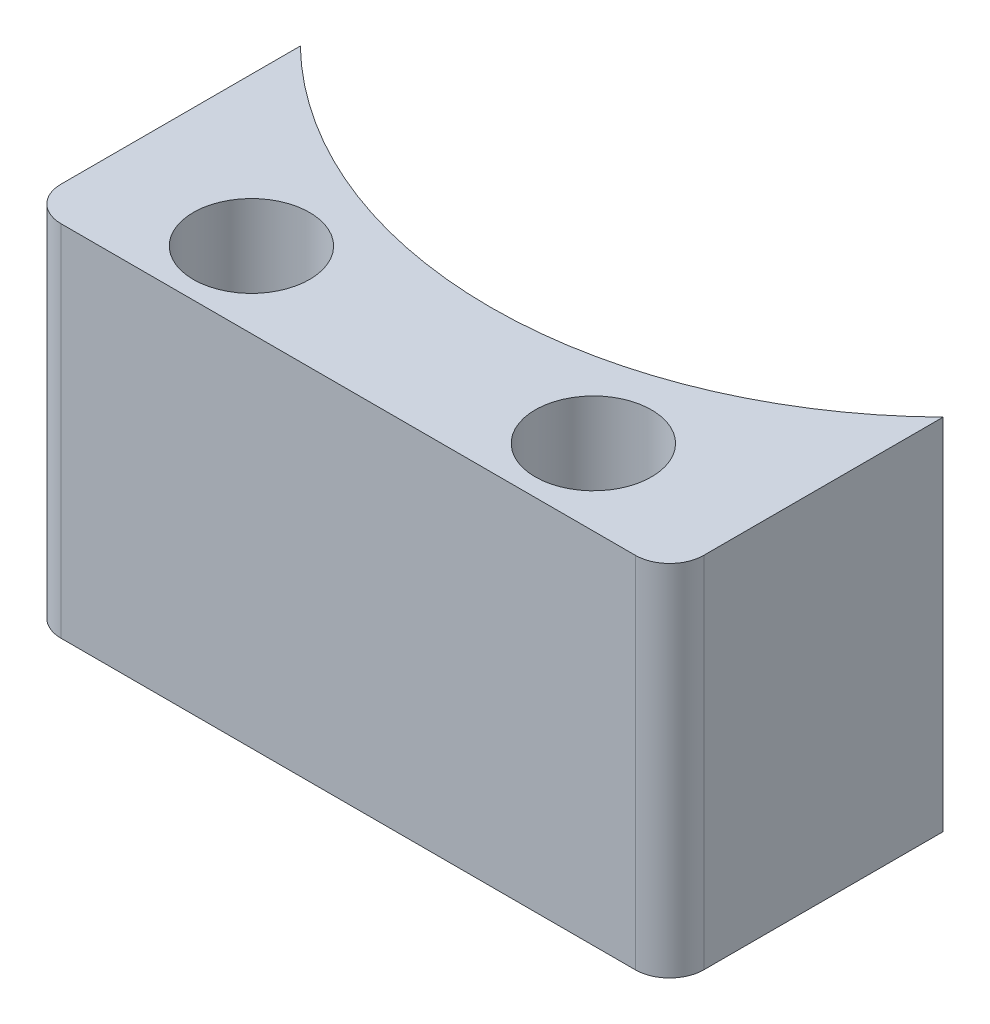
SolidWorks part; units mm, degrees
material "Сплав 2024"
ref_plane "Спереди" through (0, 0, 0) normal (0, 0, 1) x (1, 0, 0)
ref_plane "Сверху" through (0, 0, 0) normal (0, 1, 0) x (1, 0, 0)
ref_plane "Справа" through (0, 0, 0) normal (1, 0, 0) x (0, 0, -1)
sketch "Эскиз1" plane through (0, 0, 0) normal (0, 1, 0) x (1, 0, 0)
  line L0 (9.4, -8) -> (9.4, 13.6226) construction
  line L1 (0, 0) -> (18.8, 0) construction
  line L2 (0, 0) -> (0, -8)
  line L3 (0, -8) -> (18.8, -8)
  line L4 (18.8, 0) -> (18.8, -8)
  arc A0 (0, 0) -> (18.8, 0) centre (9.4, 9.6) ccw
  dimension "D3" = 17.6
  dimension "D1" = 8
  dimension "D2" = 18.8
extrude "Бобышка-Вытянуть1" add sketch "Эскиз1" along normal blind 10.5
fillet "Скругление1" radius 1 2 edges at (18.8, 5.25, 8) (0, 5.25, 8)
sketch "Эскиз2" plane through (0, 10.5, 0) normal (0, 1, 0) x (1, 0, 0)
  line L0 (0, -5.7792) -> (18.8, -5.7792) construction
  line L1 (0, 0) -> (0, -7) construction
  line L2 (18.8, -7) -> (18.8, 0) construction
  line L4 (4.3502, -8) -> (4.3502, -2.8507) construction
  line L5 (1, -8) -> (17.8, -8) construction
  line L7 (14.3502, -8) -> (14.3502, -2.8906) construction
  arc A0 (0, 0) -> (18.8, 0) centre (9.4, 9.6) ccw construction
  dimension "D1" = 2.2208
  dimension "D2" = 10
  dimension "D3" = 4.3502
hole_wizard "Отверстие с зазором M31" positions "Эскиз4" profile "Эскиз3" hole size "M3" standard "Ansi Metric" end condition up to next
sketch "Эскиз4" plane through (0, 10.5, 0) normal (0, 1, 0) x (1, 0, 0)
  line L0 (0, -5.7792) -> (18.8, -5.7792) construction
  line L1 (4.3502, -8) -> (4.3502, -2.8507) construction
  line L2 (14.3502, -8) -> (14.3502, -2.8906) construction
  point P0 (4.3502, -5.7792)
  point P6 (14.3502, -5.7792)
sketch "Эскиз3" plane through (4.3502, 10.5, 5.7792) normal (1, 0, 0) x (0, 0, 1)
  line L0 (0, 0) -> (0, 10.5)
  line L1 (0, 10.5) -> (1.7, 10.5)
  line L2 (1.7, 10.5) -> (1.7, 0)
  line L5 (1.7, 0) -> (0, 0)
  line L11 (0, -6.35) -> (0, 107.95) construction
  dimension "Диаметр сквозного отверстия" = 3.4
  dimension "Глубина сквозного отверстия" = 10.5
